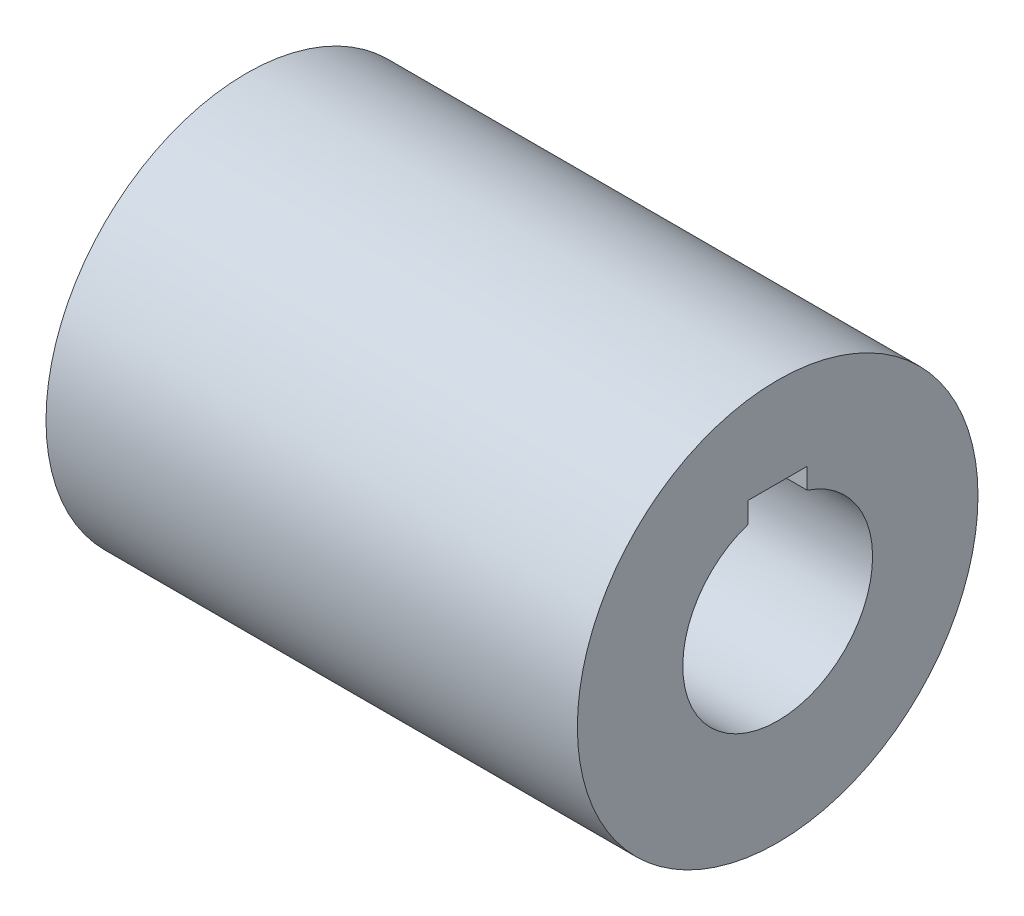
SolidWorks part; units mm, degrees
ref_plane "Front Plane" through (0, 0, 0) normal (0, 0, 1) x (1, 0, 0)
ref_plane "Top Plane" through (0, 0, 0) normal (0, 1, 0) x (1, 0, 0)
ref_plane "Right Plane" through (0, 0, 0) normal (1, 0, 0) x (0, 0, -1)
sketch "Эскиз1" plane through (0, 0, 0) normal (1, 0, 0) x (0, 0, -1)
  circle A0 centre (0, 0) radius 47.5
  dimension "D1" = 95
extrude "Бобышка-Вытянуть1" add sketch "Эскиз1" along normal mid plane 126
ref_plane "Плоскость1" through (13, 0, 0) normal (1, 0, 0) x (0, 0, -1)
ref_plane "Плоскость2" through (-13, 0, 0) normal (1, 0, 0) x (0, 0, -1)
sketch "Эскиз2" plane through (-13, 0, 0) normal (1, 0, 0) x (0, 0, -1)
  line L0 (0, 0) -> (0, 31.8) construction
  line L1 (-8, 31.8) -> (8, 31.8)
  line L2 (8, 31.8) -> (8, 26.3106)
  line L4 (-8, 26.3106) -> (-8, 31.8)
  arc A0 (-8, 26.3106) -> (8, 26.3106) centre (0, 0) ccw
  dimension "D1" = 55
  dimension "D2" = 31.8
  dimension "D3" = 16
extrude "Вырез-Вытянуть1" cut sketch "Эскиз2" against normal through all
sketch "Эскиз3" plane through (13, 0, 0) normal (1, 0, 0) x (0, 0, -1)
  line L0 (0, 0) -> (0, 26.3034) construction
  line L1 (-7, 26.3034) -> (7, 26.3034)
  line L2 (7, 26.3034) -> (7, 21.3834)
  line L4 (-7, 21.3834) -> (-7, 26.3034)
  arc A0 (-7, 21.3834) -> (7, 21.3834) centre (0, 0) ccw
  dimension "D1" = 26.3034
  dimension "D3" = 45
  dimension "D2" = 14
extrude "Вырез-Вытянуть2" cut sketch "Эскиз3" along normal through all
